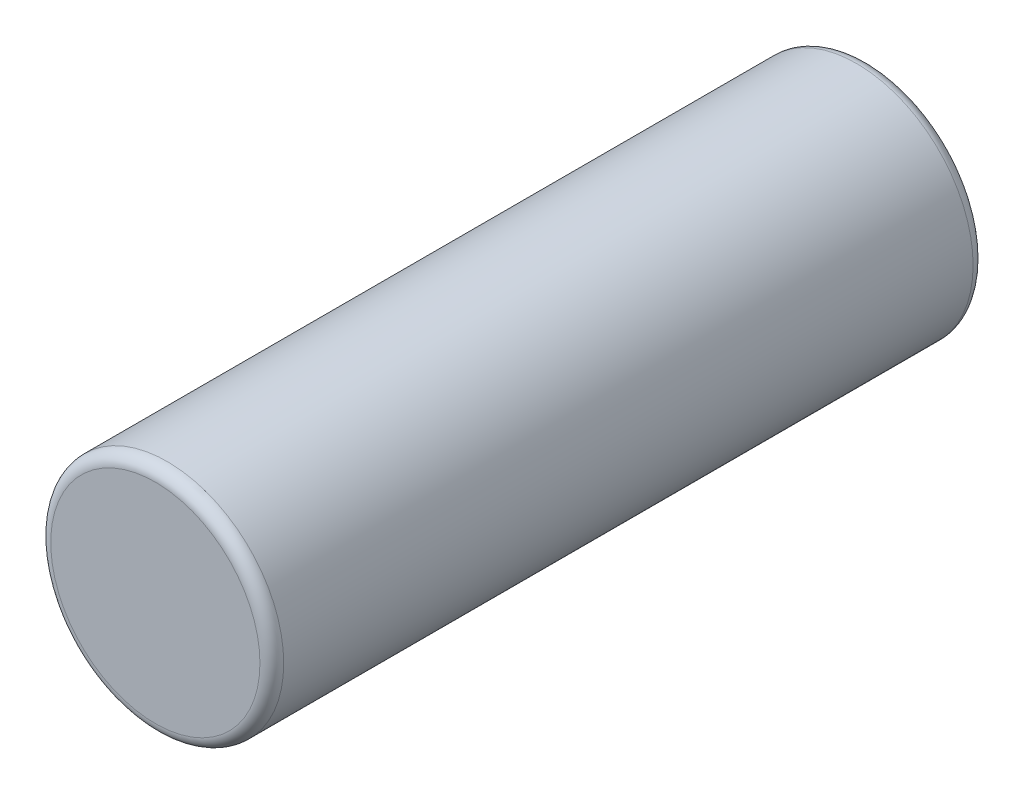
SolidWorks part; units mm, degrees
ref_plane "정면" through (0, 0, 0) normal (0, 0, 1) x (1, 0, 0)
ref_plane "윗면" through (0, 0, 0) normal (0, 1, 0) x (1, 0, 0)
ref_plane "우측면" through (0, 0, 0) normal (1, 0, 0) x (0, 0, -1)
sketch "스케치1" plane through (0, 0, 0) normal (0, 0, 1) x (1, 0, 0)
  circle A0 centre (0, 0) radius 2.45
  dimension "D1" = 4.9
extrude "보스-돌출1" add sketch "스케치1" along normal blind 15
fillet "필렛1" radius 0.25 2 edges at (2.45, 0, 15) (2.45, 0, 0)
